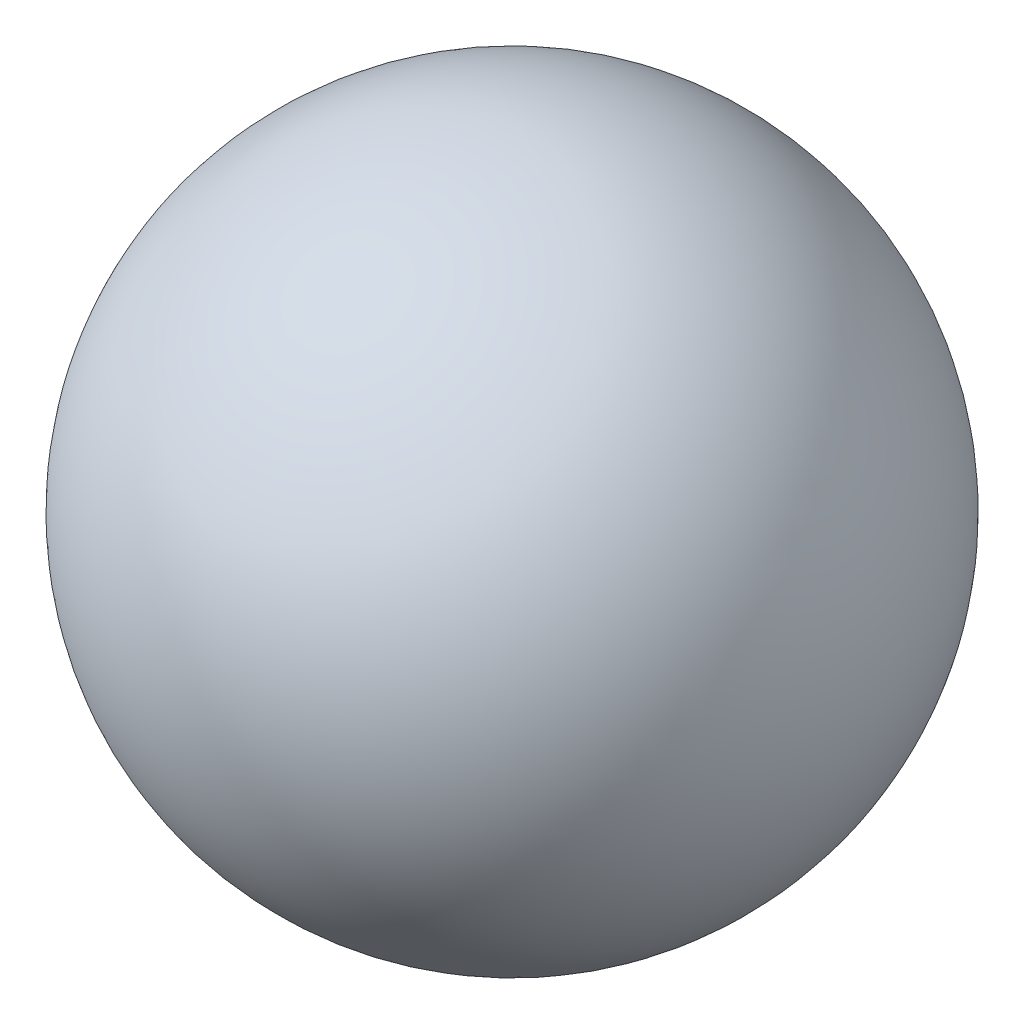
SolidWorks part; units mm, degrees
ref_plane "前视基准面" through (0, 0, 0) normal (0, 0, 1) x (1, 0, 0)
ref_plane "上视基准面" through (0, 0, 0) normal (0, 1, 0) x (1, 0, 0)
ref_plane "右视基准面" through (0, 0, 0) normal (1, 0, 0) x (0, 0, -1)
other "Configuration Table"
sketch "草图1" plane through (0, 0, 0) normal (0, 0, 1) x (1, 0, 0)
  line L0 (0, 0) -> (32, 0) construction
  line L1 (0, 0) -> (-44.9894, 0) construction
  line L2 (32, 0) -> (-32, 0)
  arc A0 (32, 0) -> (-32, 0) centre (0, 0) ccw
  dimension "D1" = 32
revolve "旋转6" add sketch "草图1" angle 360 about L2
